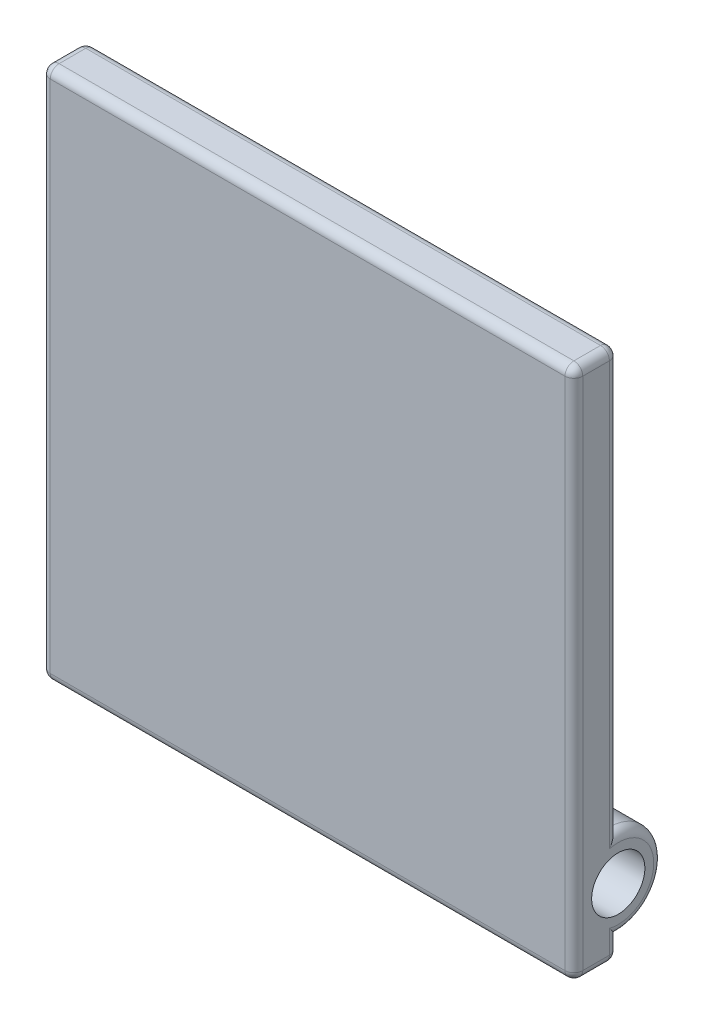
SolidWorks part; units mm, degrees
ref_plane "Front Plane" through (0, 0, 0) normal (0, 0, 1) x (1, 0, 0)
ref_plane "Top Plane" through (0, 0, 0) normal (0, 1, 0) x (1, 0, 0)
ref_plane "Right Plane" through (0, 0, 0) normal (1, 0, 0) x (0, 0, -1)
sketch "Sketch1" plane through (0, 0, 0) normal (0, 0, 1) x (1, 0, 0)
  line L1 (-76.2, -76.2) -> (76.2, -76.2)
  line L2 (-76.2, -76.2) -> (-76.2, 76.2)
  line L3 (-76.2, 76.2) -> (76.2, 76.2)
  line L4 (76.2, -76.2) -> (76.2, 76.2)
  line L5 (-76.2, -76.2) -> (76.2, 76.2) construction
  line L6 (-76.2, 76.2) -> (76.2, -76.2) construction
  point P0 (0, 0)
  dimension "D1" = 152.4
  dimension "D2" = 152.4
extrude "Boss-Extrude1" add sketch "Sketch1" along normal blind 12.7 contours L3 L4 L1 L2
sketch "Sketch2" plane through (-76.2, 0, 0) normal (-1, 0, 0) x (0, 0, 1)
  circle A0 centre (0, -57.15) radius 7.62
  dimension "D1" = 15.24
  dimension "D2" = 12.7
  dimension "D3" = 19.05
sketch "Sketch3" plane through (-76.2, 0, 0) normal (-1, 0, 0) x (0, 0, 1)
  line L0 (0, -69.85) -> (0, -44.45) construction
  line L2 (0, -69.85) -> (0, -44.45)
  line L3 (0, -76.2) -> (0, 76.2) construction
  arc A0 (0, -69.85) -> (0, -44.45) centre (0, -57.15) cw
  dimension "D1" = 12.7
  dimension "D2" = 6.35
extrude "Boss-Extrude2" add sketch "Sketch3" against normal blind 12.7 contours A0 L2
extrude "Cut-Extrude1" cut sketch "Sketch2" against normal blind 12.7
mirror "Mirror1" about plane through (0, 0, 0) normal (1, 0, 0) of "Cut-Extrude1", "Boss-Extrude2"
fillet "Fillet1" radius 2.54 1 edges at (0, -76.2, 12.7)
fillet "Fillet2" radius 2.54 19 edges at (-76.2, 15.875, 0) (0, 76.2, 0) (76.2, -76.2, 5.08) (76.2, -75.4561, 11.9561) (-76.2, -76.2, 5.08) (-76.2, 1.27, 12.7) (-76.2, 76.2, 6.35) (-76.2, -75.4561, 11.9561) (0, 76.2, 12.7) (76.2, 1.27, 12.7) (76.2, 76.2, 6.35) (-76.2, -57.15, -12.7) (-63.5, -57.15, -12.7) (-76.2, -73.025, 0) (0, -76.2, 0) (76.2, -73.025, 0) (76.2, -57.15, -12.7) (63.5, -57.15, -12.7) (76.2, 15.875, 0)
